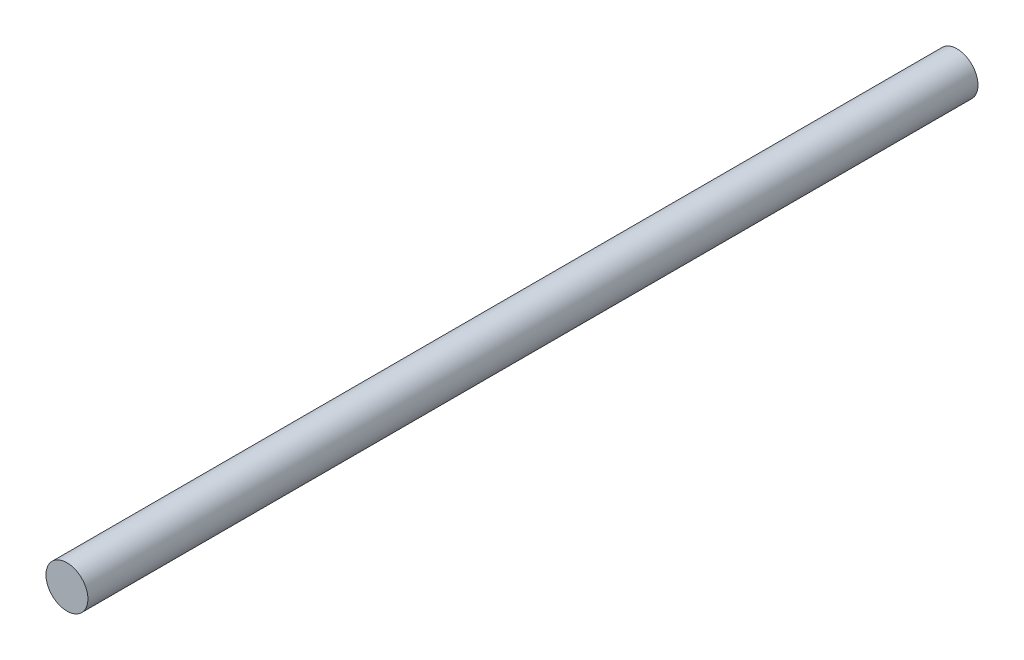
SolidWorks part; units mm, degrees
ref_plane "Front Plane" through (0, 0, 0) normal (0, 0, 1) x (1, 0, 0)
ref_plane "Top Plane" through (0, 0, 0) normal (0, 1, 0) x (1, 0, 0)
ref_plane "Right Plane" through (0, 0, 0) normal (1, 0, 0) x (0, 0, -1)
sketch "Sketch1" plane through (0, 0, 0) normal (0, 0, 1) x (1, 0, 0)
  circle A0 centre (0, 0) radius 7.185
  dimension "D1" = 14.37
extrude "Boss-Extrude1" add sketch "Sketch1" along normal blind 305
